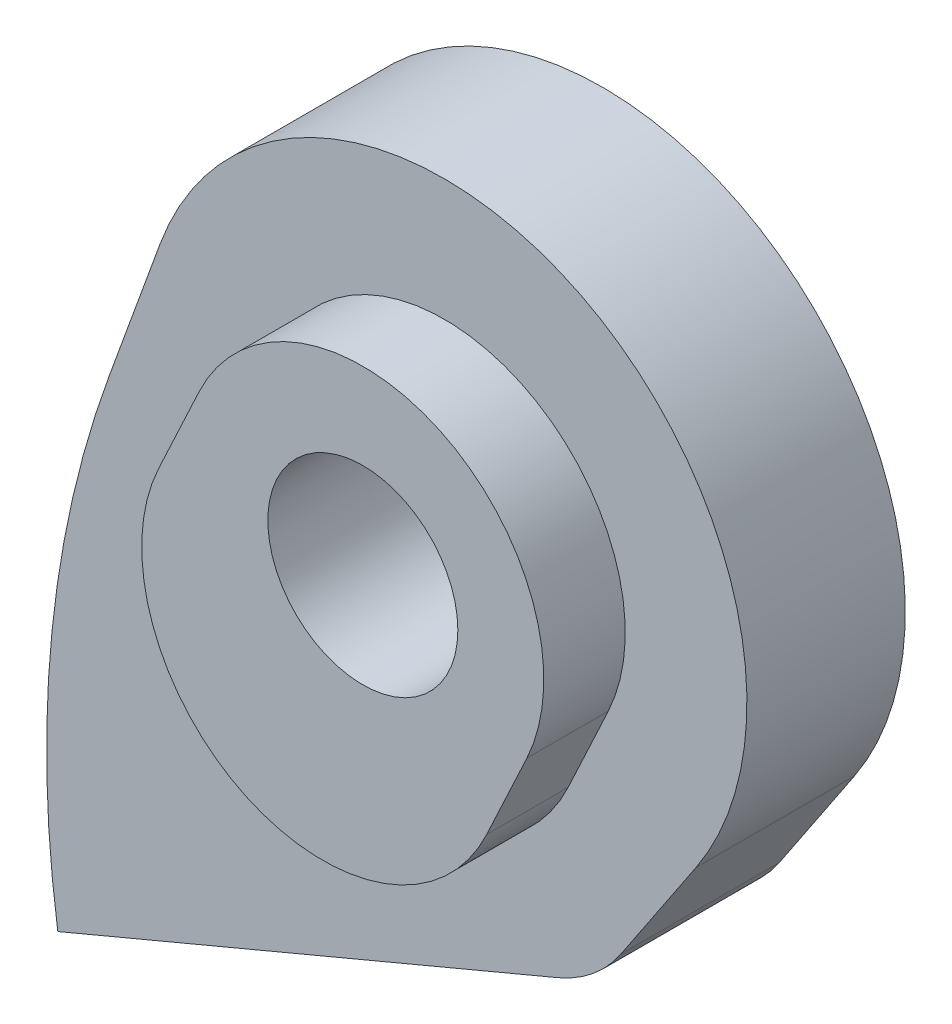
SolidWorks part; units mm, degrees
ref_plane "Front Plane" through (0, 0, 0) normal (0, 0, 1) x (1, 0, 0)
ref_plane "Top Plane" through (0, 0, 0) normal (0, 1, 0) x (1, 0, 0)
ref_plane "Right Plane" through (0, 0, 0) normal (1, 0, 0) x (0, 0, -1)
sketch "Sketch6" plane through (0, 0, 0) normal (0, 0, 1) x (1, 0, 0)
  line L0 (0, 0) -> (40.1809, 0) construction
  line L1 (0, 0) -> (35.507, 92.499) construction
  line L2 (19.3519, 50.4133) -> (0.4719, 63.0164) construction
  line L3 (19.3519, 50.4133) -> (-36.1025, 71.7003) construction
  dimension "D1" = 69
  dimension "D2" = 54
  dimension "D3" = 22.7
  dimension "D4" = 5
sketch "Sketch3" plane through (0, 0, 0) normal (0, 0, 1) x (1, 0, 0)
  line L0 (24.1743, 72.523) -> (120.8717, 72.523) construction
  line L6 (11.8164, 60.2529) -> (11.7284, 60.3116)
  line L7 (7.3748, 53.5992) -> (5.9136, 54.5745)
  line L8 (19.3519, 50.4133) -> (0.4719, 63.0164) construction
  line L9 (-6.1719, 82.4206) -> (-7.2903, 79.3479)
  line L10 (19.3519, 50.4133) -> (13.2479, 41.2693) construction
  line L11 (19.3519, 50.4133) -> (31.6629, 68.8558) construction
  line L12 (4.0204, 73.9337) -> (5.6789, 76.4182)
  line L14 (0.1147, 80.1325) -> (27.1455, 62.0885) construction
  line L15 (0.1147, 80.1325) -> (-7.2903, 79.3479) construction
  line L16 (0.1147, 80.1325) -> (0.1147, 91.1913) construction
  line L17 (0.1147, 80.1325) -> (-6.1719, 82.4206) construction
  arc A0 (13.4996, 47.0498) -> (20.2139, 57.1081) centre (19.3519, 50.4133) ccw
  arc A1 (20.2139, 57.1081) -> (11.8164, 60.2529) centre (22.7223, 76.5904) cw
  arc A2 (13.4996, 47.0498) -> (7.3748, 53.5992) centre (-3.5311, 37.2616) ccw
  arc A3 (11.7284, 60.3116) -> (6.8662, 65.9311) centre (19.4923, 71.9424) cw
  arc A4 (-6.1719, 82.4206) -> (5.6789, 76.4182) centre (0.1147, 80.1325) cw
  arc A5 (6.8662, 65.9311) -> (4.9012, 68.3908) centre (0.6246, 62.9595) ccw
  arc A6 (4.9012, 68.3908) -> (4.0204, 73.9337) centre (7.4585, 71.6386) cw
  arc A7 (5.9136, 54.5745) -> (0.4148, 56.2666) centre (0.3298, 46.2096) ccw
  arc A10 (0.4148, 56.2666) -> (-5.2798, 59.4837) centre (0.4719, 63.0164) cw
  circle A12 centre (19.3519, 50.4133) radius 2.75
  circle A13 centre (0.4719, 63.0164) radius 2.75
  circle A17 centre (0.1147, 80.1325) radius 2.1
  arc A18 (-7.2903, 79.3479) -> (-5.2798, 59.4837) centre (14.2795, 71.4971) ccw
  dimension "D1" = 5.5
  dimension "D2" = 5.5
  dimension "D3" = 4
  dimension "D5" = 4
  dimension "D6" = 4
  dimension "D4" = 4.2
  dimension "D17" = 70
  dimension "D18" = 3.27
  dimension "D14" = 6.69
  dimension "D7" = 3
  dimension "D8" = 4
  dimension "D9" = 3
  dimension "D10" = 4
  dimension "D11" = 19
  dimension "D12" = 19
  dimension "D13" = 22
  dimension "D15" = 32.5
  dimension "D16" = 14
extrude "Boss-Extrude2" add sketch "Sketch3" along normal blind 11
sketch "Sketch13" plane through (0, 0, 0) normal (0, 0, -1) x (-1, 0, 0)
  line L0 (-5.6789, 76.4182) -> (-4.0204, 73.9337)
  line L1 (-2.6258, 72.7829) -> (8.4277, 68.1397)
  line L2 (6.1719, 82.4206) -> (7.2903, 79.3479)
  arc A0 (-5.6789, 76.4182) -> (6.1719, 82.4206) centre (-0.1147, 80.1325) cw
  arc A1 (6.1719, 82.4206) -> (-5.6789, 76.4182) centre (-0.1147, 80.1325) ccw construction
  arc A2 (-4.0204, 73.9337) -> (-2.6258, 72.7829) centre (-1.4106, 75.6758) ccw
  arc A3 (5.2798, 59.4837) -> (7.2903, 79.3479) centre (-14.2795, 71.4971) ccw construction
  arc A4 (8.4277, 68.1397) -> (7.2903, 79.3479) centre (-14.2795, 71.4971) ccw
extrude "Boss-Extrude4" add sketch "Sketch13" along normal blind 3.5
sketch "Sketch12" plane through (0, 0, -3.5) normal (0, 0, -1) x (-1, 0, 0)
  line L0 (8.0136, 76.9658) -> (4.9242, 69.6114)
  line L4 (4.9242, 69.6114) -> (8.4277, 68.1397)
  line L5 (-2.6258, 72.7829) -> (8.4277, 68.1397) construction
  line L8 (-2.6258, 72.7829) -> (8.4277, 68.1397) construction
  arc A0 (8.0136, 76.9658) -> (8.4277, 68.1397) centre (-14.2795, 71.4971) cw
  arc A1 (5.2798, 59.4837) -> (8.4277, 68.1397) centre (-14.2795, 71.4971) ccw construction
  dimension "D1" = 3.8
  dimension "D2" = 90
extrude "Boss-Extrude3" add sketch "Sketch12" along normal blind 3
sketch "Sketch14" plane through (0, 0, 0) normal (0, 1, 0) x (1, 0, 0)
  line L0 (19.3519, 0) -> (-36.1025, 0) construction
  line L1 (-15.2308, 0) -> (32.0549, 0)
  line L2 (-15.2308, 0) -> (-15.2308, -12.5955)
  line L3 (-15.2308, -12.5955) -> (32.0549, -12.5955)
  line L4 (32.0549, 0) -> (32.0549, -12.5955)
extrude "Cut-Extrude1" cut sketch "Sketch14" along normal through all
sketch "Sketch16" plane through (0, 0, 0) normal (0, 0, 1) x (1, 0, 0)
  line L0 (0.1147, 80.1325) -> (-0.7728, 78.2293) construction
  line L1 (3.7399, 78.4421) -> (2.8524, 76.5388)
  line L2 (-3.5105, 81.823) -> (-4.398, 79.9198)
  line L3 (0.1147, 80.1325) -> (0.1147, 75.6752) construction
  arc A0 (3.7399, 78.4421) -> (-3.5105, 81.823) centre (0.1147, 80.1325) ccw
  arc A1 (-4.398, 79.9198) -> (2.8524, 76.5388) centre (-0.7728, 78.2293) ccw
  point P3 (-0.3291, 79.1809)
  dimension "D1" = 4
  dimension "D2" = 25
  dimension "D3" = 2.1
extrude "Boss-Extrude5" add sketch "Sketch16" along normal blind 1.8
sketch "Sketch15" plane through (0, 0, 1.8) normal (0, 0, 1) x (1, 0, 0)
  circle A0 centre (0.1147, 80.1325) radius 2.1
  dimension "D1" = 4.2
extrude "Cut-Extrude2" cut sketch "Sketch15" against normal through all
